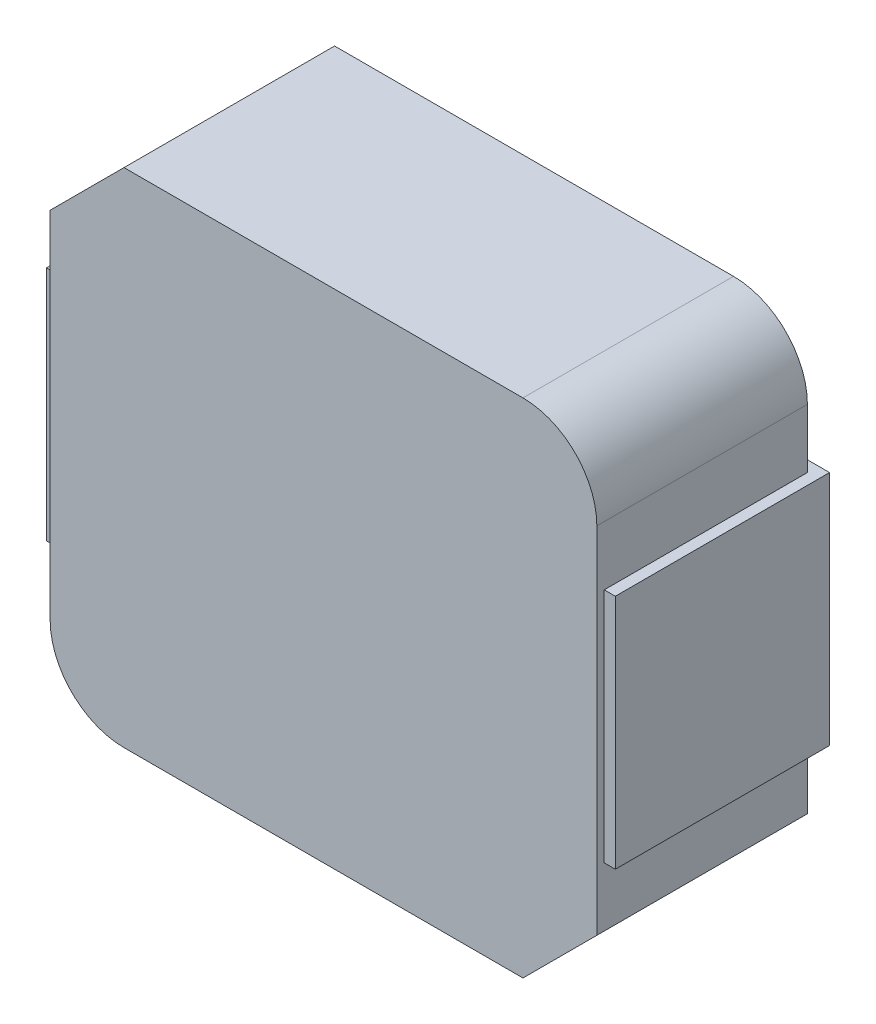
SolidWorks part; units mm, degrees
ref_plane "Plan de face" through (0, 0, 0) normal (0, 0, 1) x (1, 0, 0)
ref_plane "Plan de dessus" through (0, 0, 0) normal (0, 1, 0) x (1, 0, 0)
ref_plane "Plan de droite" through (0, 0, 0) normal (1, 0, 0) x (0, 0, -1)
sketch "Sketch1" plane through (0, 0, 0) normal (0, 0, 1) x (1, 0, 0)
  line L1 (-3.7, 3.4) -> (3.7, 3.4)
  line L2 (-3.7, 3.4) -> (-3.7, -3.4)
  line L3 (-3.7, -3.4) -> (3.7, -3.4)
  line L4 (3.7, 3.4) -> (3.7, -3.4)
  line L5 (-3.7, 3.4) -> (3.7, -3.4) construction
  line L6 (-3.7, -3.4) -> (3.7, 3.4) construction
  point P0 (0, 0)
  dimension "D1" = 6.8
  dimension "D2" = 7.4
extrude "Boss-Extrude1" add sketch "Sketch1" along normal blind 2.85 from offset 0.15
fillet "Fillet1" radius 1 2 edges at (-3.7, -3.4, 1.575) (3.7, 3.4, 1.575)
chamfer "Chamfer1" distance 1 angle 45 2 edges at (3.7, -3.4, 1.575) (-3.7, 3.4, 1.575)
sketch "Sketch2" plane through (0, 0, 0) normal (0, 1, 0) x (1, 0, 0)
  line L0 (2, -0.15) -> (3.7, -0.15)
  line L1 (2.7, -0.15) -> (-2.7, -0.15) construction
  line L2 (3.7, -0.15) -> (3.7, -2.9)
  line L3 (3.7, -0.15) -> (3.7, -3) construction
  line L4 (3.7, -2.9) -> (3.85, -2.9)
  line L5 (3.85, -2.9) -> (3.85, 0)
  line L6 (3.85, 0) -> (2, 0)
  line L7 (2, 0) -> (2, -0.15)
  line L8 (2.7, -3) -> (3.7, -3) construction
  dimension "D1" = 0.15
  dimension "D2" = 1.85
  dimension "D3" = 0.1
extrude "Boss-Extrude2" add sketch "Sketch2" along normal mid plane 3.2
mirror "Mirror1" about plane through (0, 0, 0) normal (1, 0, 0) of "Boss-Extrude2"
